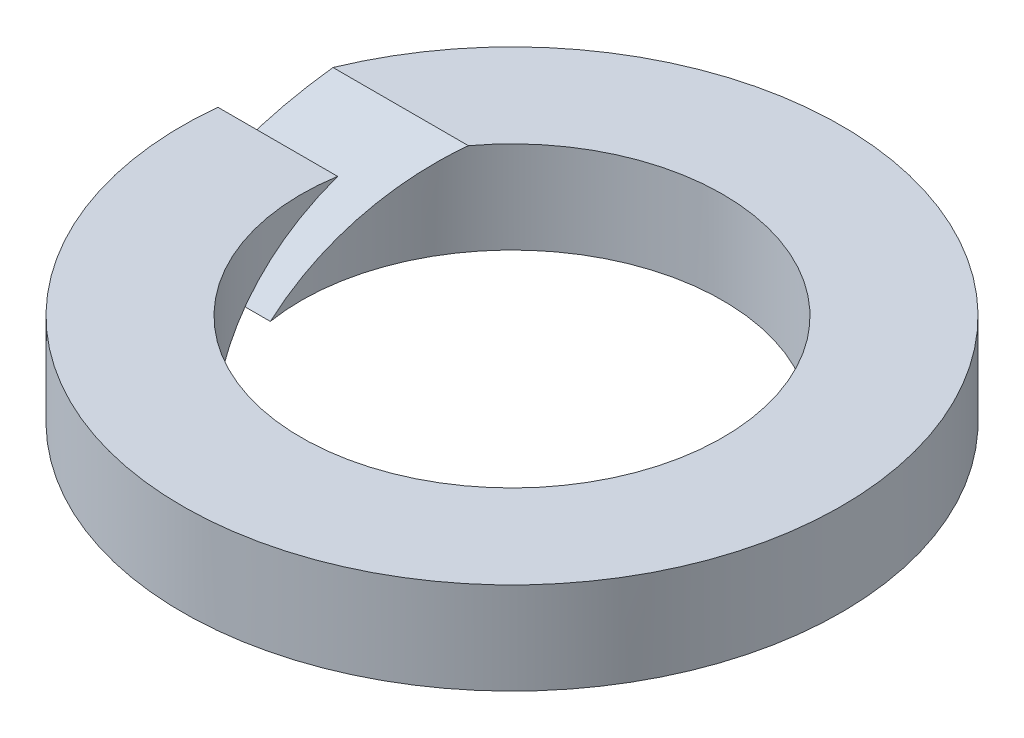
SolidWorks part; units mm, degrees
material "Alloy Steel"
ref_plane "정면" through (0, 0, 0) normal (0, 0, 1) x (1, 0, 0)
ref_plane "윗면" through (0, 0, 0) normal (0, 1, 0) x (1, 0, 0)
ref_plane "우측면" through (0, 0, 0) normal (1, 0, 0) x (0, 0, -1)
sketch "Sketch1" plane through (0, 0, 0) normal (0, 1, 0) x (1, 0, 0)
  circle A0 centre (0, 0) radius 13.75
  circle A1 centre (0, 0) radius 21.5
  circle A2 centre (0, 0) radius 13.5 construction
  dimension "M" = 27
  dimension "ID" = 27.5
  dimension "OD" = 43
extrude "Extrude1" add sketch "Sketch1" along normal blind 6
sketch "Sketch2" plane through (0, 0, 0) normal (1, 0, 0) x (0, 0, -1)
  line L0 (-8.1962, 0) -> (-2.1962, 0)
  line L1 (-8.1962, 0) -> (2.1962, 6)
  line L2 (-2.1962, 0) -> (8.1962, 6)
  line L3 (2.1962, 6) -> (8.1962, 6)
  line L4 (21.5, 6) -> (-21.5, 6) construction
  line L5 (-21.5, 0) -> (21.5, 0) construction
  line L6 (2.1962, 6) -> (-2.1962, 0) construction
  point P8 (0, 3)
  dimension "D1" = 3
  dimension "D2" = 30
extrude "Extrude2" cut sketch "Sketch2" against normal through all
equation "\"Mass\"= \"SW-질량\" / 1000"
equation "\"D1@Sketch2\"= 0.5 * \"T@Extrude1\""
